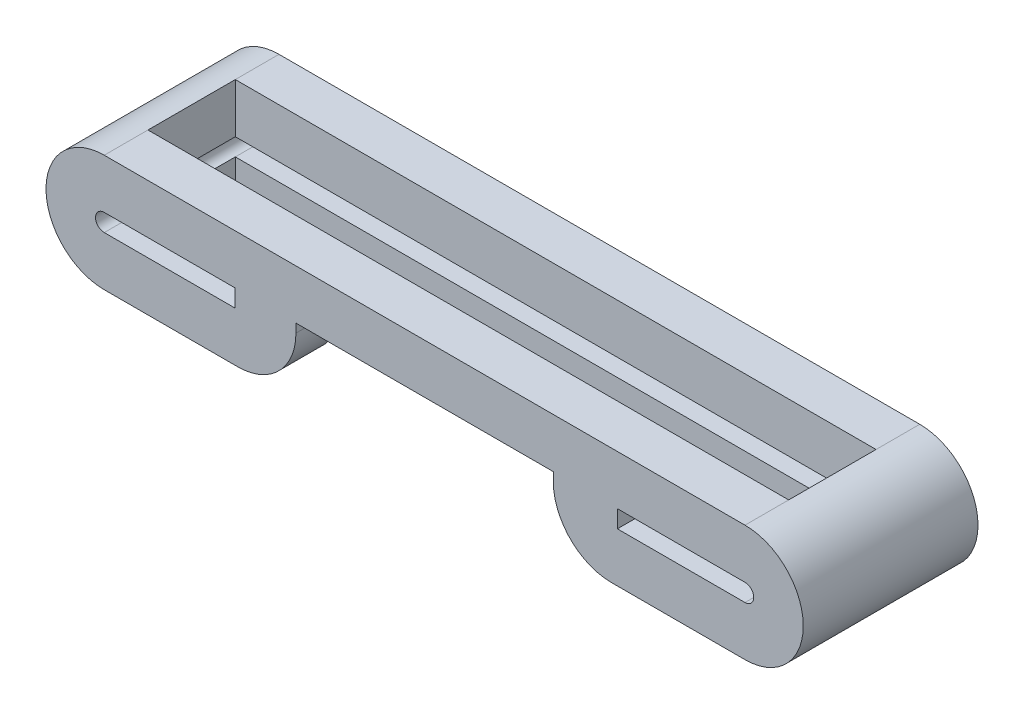
SolidWorks part; units mm, degrees
ref_plane "Plan de face" through (0, 0, 0) normal (0, 0, 1) x (1, 0, 0)
ref_plane "Plan de dessus" through (0, 0, 0) normal (0, 1, 0) x (1, 0, 0)
ref_plane "Plan de droite" through (0, 0, 0) normal (1, 0, 0) x (0, 0, -1)
sketch "Esquisse1" plane through (0, 0, 0) normal (0, 0, 1) x (1, 0, 0)
  line L0 (-55, 0) -> (55, 0) construction
  line L1 (-55, 10) -> (55, 10)
  line L2 (-55, -10) -> (55, -10)
  line L3 (-55, 0) -> (55, 0) construction
  line L4 (-55, 1.5) -> (55, 1.5)
  line L5 (-55, -1.5) -> (55, -1.5)
  arc A0 (-55, 10) -> (-55, -10) centre (-55, 0) ccw
  arc A1 (55, -10) -> (55, 10) centre (55, 0) ccw
  arc A2 (-55, 1.5) -> (-55, -1.5) centre (-55, 0) ccw
  arc A3 (55, -1.5) -> (55, 1.5) centre (55, 0) ccw
  point P2 (0, 0)
  point P10 (0, 0)
  dimension "D1" = 10
  dimension "D2" = 1.5
  dimension "D3" = 110
extrude "Boss.-Extru.1" add sketch "Esquisse1" along normal blind 30
sketch "Esquisse2" plane through (0, 10, 0) normal (0, 1, 0) x (1, 0, 0)
  line L0 (0, 0) -> (0, -30) construction
  line L1 (55, -30) -> (-55, -30) construction
  line L2 (-55, -30) -> (-55, 0) construction
  line L3 (-55, -7.5) -> (55, -7.5)
  line L4 (-55, -7.5) -> (-55, -22.5)
  line L5 (-55, -22.5) -> (55, -22.5)
  line L6 (55, -7.5) -> (55, -22.5)
  line L7 (-55, -7.5) -> (55, -22.5) construction
  line L8 (-55, -22.5) -> (55, -7.5) construction
  point P5 (0, -15)
  dimension "D1" = 15
extrude "Enlèv. mat.-Extru.1" cut sketch "Esquisse2" against normal blind 30
sketch "Esquisse3" plane through (0, 10, 0) normal (0, 1, 0) x (1, 0, 0)
  line L0 (-55, -22.5) -> (55, -22.5) construction
  line L1 (-22.095, -30) -> (22.095, -30)
  line L2 (-22.095, -30) -> (-22.095, -22.5)
  line L3 (-22.095, -22.5) -> (22.095, -22.5)
  line L4 (22.095, -30) -> (22.095, -22.5)
  line L5 (-22.095, -30) -> (22.095, -22.5) construction
  line L6 (-22.095, -22.5) -> (22.095, -30) construction
  line L7 (55, -30) -> (-55, -30) construction
  line L8 (-65, 0) -> (-65, -30) construction
  line L9 (-55, -7.5) -> (-55, -22.5) construction
  line L10 (55, -30) -> (55, -22.5) construction
  point P0 (0, -26.25)
  dimension "D1" = 44.19
extrude "Enlèv. mat.-Extru.2" cut sketch "Esquisse3" against normal blind 10 from offset 10 offset against normal yes
sketch "Esquisse4" plane through (0, -1.5, 0) normal (0, 1, 0) x (1, 0, 0)
  line L0 (-27.095, -22.5) -> (-27.095, -30)
  line L1 (27.095, -22.5) -> (27.095, -30)
  line L4 (-22.095, -30) -> (-22.095, -22.5)
  line L5 (-22.095, -22.5) -> (-55, -22.5)
  line L6 (-55, -22.5) -> (-55, -30)
  line L7 (-55, -30) -> (-22.095, -30)
  line L8 (-22.095, -30) -> (-22.095, -22.5)
  line L9 (-22.095, -22.5) -> (-27.095, -22.5)
  line L11 (-27.095, -30) -> (-22.095, -30)
  line L12 (22.095, -22.5) -> (22.095, -30)
  line L13 (22.095, -30) -> (55, -30)
  line L14 (55, -30) -> (55, -22.5)
  line L15 (55, -22.5) -> (22.095, -22.5)
  line L16 (22.095, -22.5) -> (22.095, -30)
  line L17 (22.095, -30) -> (27.095, -30)
  line L19 (27.095, -22.5) -> (22.095, -22.5)
  dimension "D3" = 5
  dimension "D4" = 5
  dimension "D1" = 0
  dimension "D2" = 0
extrude "Boss.-Extru.2" add sketch "Esquisse4" along normal blind 10
sketch "Esquisse5" plane through (27.095, 0, 0) normal (1, 0, 0) x (0, 0, -1)
  line L4 (-22.5, 1.5) -> (-30, 1.5)
  line L5 (-30, 1.5) -> (-30, -1.5)
  line L6 (-30, -1.5) -> (-22.5, -1.5)
  line L7 (-22.5, -1.5) -> (-22.5, 1.5)
  line L8 (-22.5, 1.5) -> (-30, 1.5)
  line L9 (-30, 1.5) -> (-30, -1.5)
  line L10 (-30, -1.5) -> (-22.5, -1.5)
  line L11 (-22.5, -1.5) -> (-22.5, 1.5)
  dimension "D1" = 0
extrude "Boss.-Extru.3" add sketch "Esquisse5" along normal blind 6
sketch "Esquisse6" plane through (-27.095, 0, 0) normal (-1, 0, 0) x (0, 0, 1)
  line L4 (30, 1.5) -> (22.5, 1.5)
  line L5 (22.5, 1.5) -> (22.5, -1.5)
  line L6 (22.5, -1.5) -> (30, -1.5)
  line L7 (30, -1.5) -> (30, 1.5)
  line L8 (30, 1.5) -> (22.5, 1.5)
  line L9 (22.5, 1.5) -> (22.5, -1.5)
  line L10 (22.5, -1.5) -> (30, -1.5)
  line L11 (30, -1.5) -> (30, 1.5)
  dimension "D1" = 0
extrude "Boss.-Extru.4" add sketch "Esquisse6" along normal blind 5.5
fillet "Congé1" radius 10 2 edges at (-22.095, -10, 26.25) (22.095, -10, 26.25)
